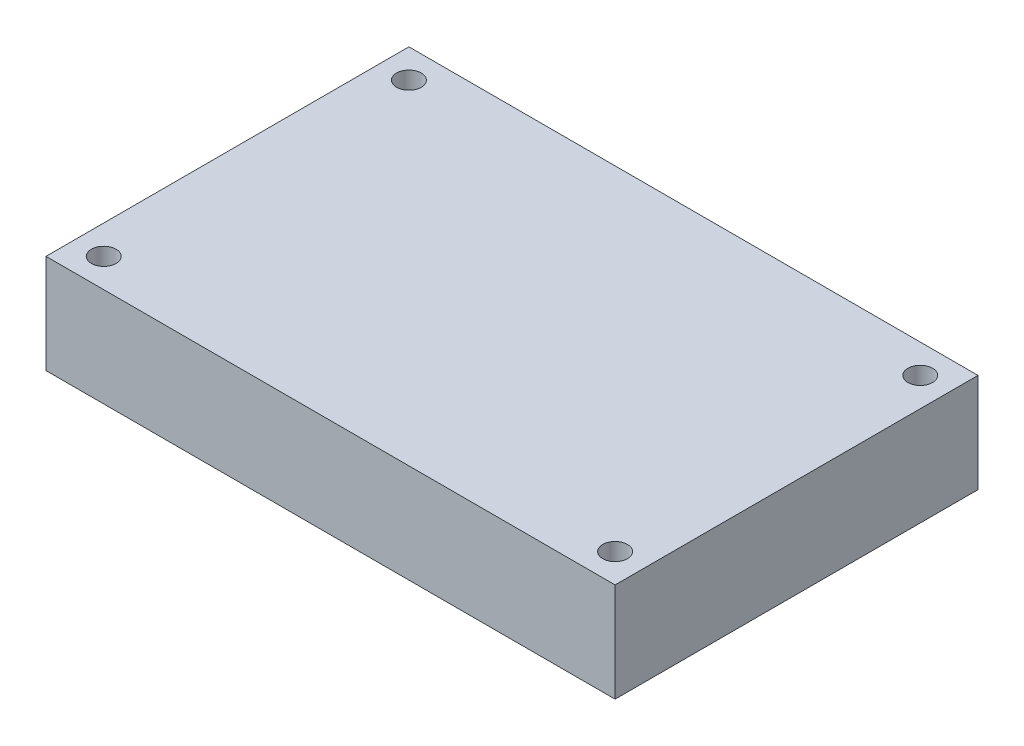
SolidWorks part; units mm, degrees
ref_plane "前视基准面" through (0, 0, 0) normal (0, 0, 1) x (1, 0, 0)
ref_plane "上视基准面" through (0, 0, 0) normal (0, 1, 0) x (1, 0, 0)
ref_plane "右视基准面" through (0, 0, 0) normal (1, 0, 0) x (0, 0, -1)
other "Configuration Table"
sketch "草图1" plane through (0, 0, 0) normal (0, 1, 0) x (1, 0, 0)
  line L1 (-34.5, 22) -> (34.5, 22)
  line L2 (-34.5, 22) -> (-34.5, -22)
  line L3 (-34.5, -22) -> (34.5, -22)
  line L4 (34.5, 22) -> (34.5, -22)
  line L5 (-34.5, 22) -> (34.5, -22) construction
  line L6 (-34.5, -22) -> (34.5, 22) construction
  point P0 (0, 0)
  dimension "D1" = 69
  dimension "D2" = 44
extrude "凸台-拉伸1" add sketch "草图1" along normal blind 12
sketch "草图2" plane through (0, 12, 0) normal (0, 1, 0) x (1, 0, 0)
  line L0 (0, 0) -> (50000, 0) construction
  line L1 (0, 0) -> (0, -50000) construction
  line L2 (-34.5, 22) -> (-34.5, -22) construction
  line L3 (34.5, 22) -> (-34.5, 22) construction
  circle A0 centre (-31, 18.5) radius 1.5
  circle A1 centre (-31, -18.5) radius 1.5
  circle A2 centre (31, -18.5) radius 1.5
  circle A3 centre (31, 18.5) radius 1.5
  dimension "D1" = 3
  dimension "D2" = 3.5
  dimension "D3" = 3.5
extrude "切除-拉伸1" cut sketch "草图2" against normal through all
